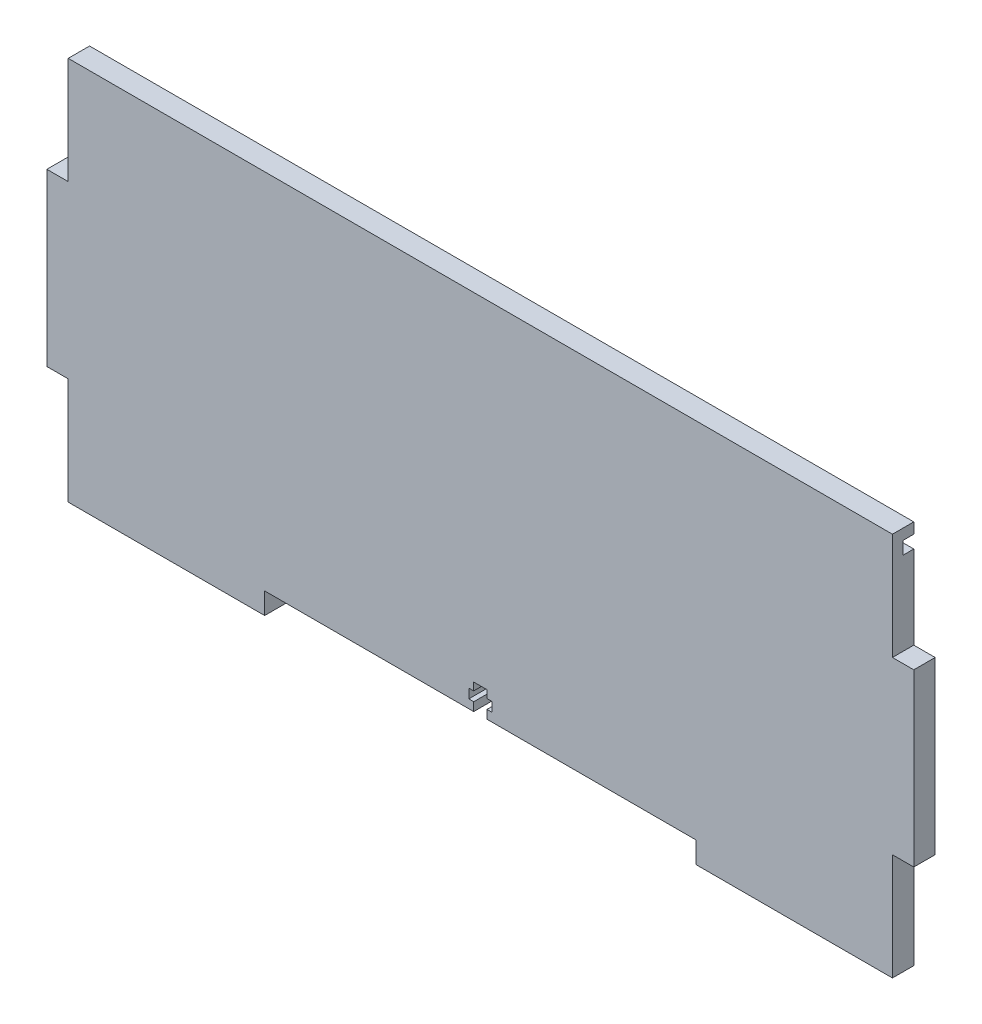
SolidWorks part; units mm, degrees
ref_plane "Front Plane" through (0, 0, 0) normal (0, 0, 1) x (1, 0, 0)
ref_plane "Top Plane" through (0, 0, 0) normal (0, 1, 0) x (1, 0, 0)
ref_plane "Right Plane" through (0, 0, 0) normal (1, 0, 0) x (0, 0, -1)
sketch "Sketch1" plane through (0, 0, 0) normal (0, 0, 1) x (1, 0, 0)
  line L1 (0, 0) -> (203, 0)
  line L2 (0, 0) -> (0, 90)
  line L3 (0, 90) -> (203, 90)
  line L4 (203, 0) -> (203, 90)
  dimension "D1" = 90
  dimension "D2" = 203
extrude "Boss-Extrude1" add sketch "Sketch1" along normal blind 5
sketch "Sketch3" plane through (0, 0, 0) normal (0, 0, -1) x (-1, 0, 0)
  line L0 (-203, 0) -> (-203, 90) construction
  line L1 (-203, 0) -> (-198, 0)
  line L2 (-203, 0) -> (-203, 25)
  line L3 (-203, 25) -> (-198, 25)
  line L4 (-198, 0) -> (-198, 25)
  line L5 (-203, 65) -> (-198, 65)
  line L6 (-203, 65) -> (-203, 90)
  line L7 (-203, 90) -> (-198, 90)
  line L8 (-198, 65) -> (-198, 90)
  line L9 (0, 0) -> (-203, 0) construction
  line L10 (0, 90) -> (0, 0) construction
  line L11 (0, 0) -> (-5, 0)
  line L12 (0, 0) -> (0, 25)
  line L13 (0, 25) -> (-5, 25)
  line L14 (-5, 0) -> (-5, 25)
  line L15 (0, 65) -> (-5, 65)
  line L16 (0, 65) -> (0, 90)
  line L17 (0, 90) -> (-5, 90)
  line L18 (-5, 65) -> (-5, 90)
  line L20 (-152, 0) -> (-51, 0)
  line L21 (-152, 0) -> (-152, 5)
  line L22 (-152, 5) -> (-51, 5)
  line L23 (-51, 0) -> (-51, 5)
  dimension "D1" = 5
  dimension "D2" = 25
  dimension "D3" = 25
  dimension "D4" = 5
  dimension "D5" = 65
  dimension "D6" = 5
  dimension "D7" = 25
  dimension "D8" = 5
  dimension "D9" = 25
  dimension "D10" = 65
  dimension "D11" = 5
  dimension "D12" = 101
  dimension "D13" = 51
  dimension "D14" = 193
extrude "Cut-Extrude2" cut sketch "Sketch3" against normal through all
sketch "Sketch4" plane through (0, 0, 0) normal (0, 0, -1) x (-1, 0, 0)
  line L0 (-198, 65) -> (-198, 90) construction
  line L1 (-198, 87.5) -> (-5, 87.5)
  line L2 (-198, 87.5) -> (-198, 84.5)
  line L3 (-198, 84.5) -> (-5, 84.5)
  line L4 (-5, 87.5) -> (-5, 84.5)
  line L5 (-5, 90) -> (-5, 65) construction
  line L6 (-198, 90) -> (-5, 90) construction
  dimension "D1" = 3
  dimension "D2" = 2.5
extrude "Cut-Extrude3" cut sketch "Sketch4" against normal blind 2.5
sketch "Sketch5" plane through (0, 0, 0) normal (0, 0, -1) x (-1, 0, 0)
  line L0 (-51, 5) -> (-152, 5) construction
  line L1 (-152, 5) -> (-152, 0) construction
  line L4 (-99.95, 11) -> (-103.05, 11)
  line L5 (-99.95, 11) -> (-99.95, 5)
  line L6 (-99.95, 5) -> (-103.05, 5)
  line L7 (-103.05, 11) -> (-103.05, 5)
  line L12 (-98.8, 7) -> (-104.2, 7)
  line L13 (-98.8, 7) -> (-98.8, 9.2)
  line L14 (-98.8, 9.2) -> (-104.2, 9.2)
  line L15 (-104.2, 7) -> (-104.2, 9.2)
  line M16 (-152, 5) -> (-51, 5)
  dimension "D1" = 5.4
  dimension "D2" = 2.2
  dimension "D3" = 6
  dimension "D4" = 3.1
  dimension "D5" = 1.8
  dimension "D6" = 1.15
  dimension "D7" = 0
  dimension "D8" = 48.95
extrude "Cut-Extrude4" cut sketch "Sketch5" against normal through all contours L14 L5 L4 L7 | L15 L12 L7 L14 | L5 L14 L7 L12 | L13 L14 L5 L12 | L5 L12 L7 M16
equation "\"D8@Sketch5\"=(101-3.1)/2"
